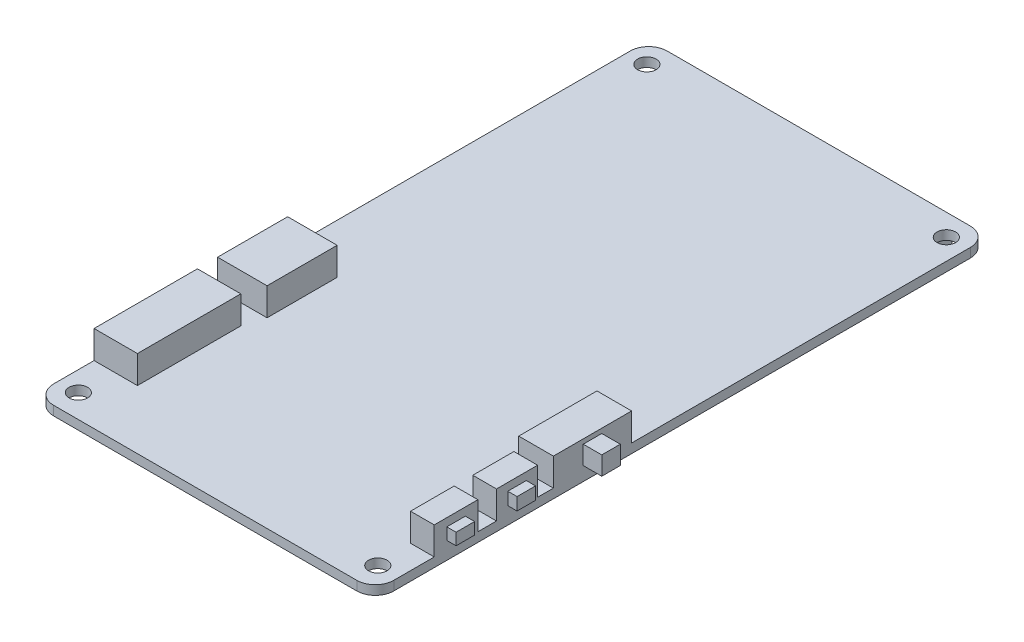
SolidWorks part; units mm, degrees
ref_plane "Front Plane" through (0, 0, 0) normal (0, 0, 1) x (1, 0, 0)
ref_plane "Top Plane" through (0, 0, 0) normal (0, 1, 0) x (1, 0, 0)
ref_plane "Right Plane" through (0, 0, 0) normal (1, 0, 0) x (0, 0, -1)
sketch "Sketch5" plane through (0, 0, 0) normal (0, 1, 0) x (1, 0, 0)
  line L1 (0, 0) -> (36.75, 0)
  line L2 (0, 0) -> (0, 66.29)
  line L3 (0, 66.29) -> (36.75, 66.29)
  line L4 (36.75, 0) -> (36.75, 66.29)
  dimension "D1" = 36.75
  dimension "D2" = 66.29
extrude "Boss-Extrude3" add sketch "Sketch5" along normal blind 1
fillet "Fillet1" radius 2 1 edges at (0, 0.5, 0)
fillet "Fillet2" radius 2 3 edges at (0, 0.5, -66.29) (36.75, 0.5, -66.29) (36.75, 0.5, 0)
sketch "Sketch7" plane through (0, 1, 0) normal (0, 1, 0) x (1, 0, 0)
  line L0 (0, 2.52) -> (36.75, 2.52)
  line L1 (0, 64.29) -> (0, 2) construction
  line L2 (36.75, 2) -> (36.75, 64.29) construction
  line L3 (2, 0) -> (34.75, 0) construction
  line L4 (0, 63.94) -> (36.75, 63.94)
  line L5 (34.75, 66.29) -> (2, 66.29) construction
  line L6 (2.15, 66.29) -> (2.15, 0)
  line L7 (34.5, 66.29) -> (34.5, 0)
  circle A0 centre (2.15, 63.94) radius 1
  circle A1 centre (34.5, 63.94) radius 1
  circle A2 centre (2.15, 2.52) radius 1
  circle A3 centre (34.5, 2.52) radius 1
  point P18 (0, 0)
  dimension "D5" = 2
  dimension "D6" = 2
  dimension "D7" = 2
  dimension "D8" = 2
  dimension "D1" = 2.52
  dimension "D2" = 2.35
  dimension "D3" = 2.15
  dimension "D4" = 2.25
extrude "Cut-Extrude1" cut sketch "Sketch7" against normal blind 2 contours A0 | A1 | A3 | A2
sketch "Sketch9" plane through (0, 1, 0) normal (0, 1, 0) x (1, 0, 0)
  line L0 (41.1667, 224.0946) -> (205.8333, 224.0946) construction
  line L1 (0, 64.29) -> (0, 2) construction
  line L2 (0, 6.3692) -> (4.6839, 6.3692)
  line L3 (0, 6.3692) -> (0, 17.5362)
  line L4 (0, 17.5362) -> (4.6839, 17.5362)
  line L5 (4.6839, 6.3692) -> (4.6839, 17.5362)
  line L6 (2, 0) -> (34.75, 0) construction
  line L7 (36.75, 2) -> (36.75, 64.29) construction
  line L8 (0, 27.2836) -> (5.3464, 27.2836)
  line L9 (0, 27.2836) -> (0, 19.7128)
  line L10 (0, 19.7128) -> (5.3464, 19.7128)
  line L11 (5.3464, 27.2836) -> (5.3464, 19.7128)
  line L12 (36.75, 27.6919) -> (33.0063, 27.6919)
  line L13 (36.75, 27.6919) -> (36.75, 19.2413)
  line L14 (36.75, 19.2413) -> (33.0063, 19.2413)
  line L15 (33.0063, 27.6919) -> (33.0063, 19.2413)
  line L17 (36.75, 17.5362) -> (34.1882, 17.5362)
  line L18 (36.75, 17.5362) -> (36.75, 13.0955)
  line L19 (36.75, 13.0955) -> (34.1882, 13.0955)
  line L20 (34.1882, 17.5362) -> (34.1882, 13.0955)
  line L21 (36.75, 11.0862) -> (34.1882, 11.0862)
  line L22 (36.75, 11.0862) -> (36.75, 6.3692)
  line L23 (36.75, 6.3692) -> (34.1882, 6.3692)
  line L24 (34.1882, 11.0862) -> (34.1882, 6.3692)
  point P28 (0, 0)
  point P29 (4.6839, 17.5362)
  point P30 (0, 0)
  line M15 (0, 64.29) -> (0, 2)
  line M19 (36.75, 2) -> (36.75, 64.29)
  dimension "D1" = 11.1669
  dimension "D2" = 4.6839
  dimension "D3" = 6.3692
  dimension "D4" = 5.3464
  dimension "D5" = 7.5708
  dimension "D6" = 19.7128
  dimension "D7" = 3.7437
  dimension "D8" = 8.4506
  dimension "D9" = 19.2413
extrude "Boss-Extrude5" add sketch "Sketch9" along normal blind 3 contours L2 L5 L4 M15 | L12 L15 L14 M19 | L17 L20 L19 M19 | L21 L24 L23 M19 | L8 L11 L10 L9
sketch "Sketch11" plane through (36.75, 0, 0) normal (1, 0, 0) x (0, 0, -1)
  line L0 (11.0862, 1) -> (6.3692, 4) construction
  line L1 (11.0862, 4) -> (6.3692, 1) construction
  line L2 (13.0955, 4) -> (17.5362, 1) construction
  line L3 (13.0955, 1) -> (17.5362, 4) construction
  line L4 (17.5362, 4) -> (17.5362, 1) construction
  line L6 (7.7277, 1.864) -> (9.7277, 1.864)
  line L7 (7.7277, 1.864) -> (7.7277, 3.136)
  line L8 (7.7277, 3.136) -> (9.7277, 3.136)
  line L9 (9.7277, 1.864) -> (9.7277, 3.136)
  line L10 (7.7277, 1.864) -> (9.7277, 3.136) construction
  line L11 (7.7277, 3.136) -> (9.7277, 1.864) construction
  line L12 (14.3158, 1.8244) -> (16.3158, 1.8244)
  line L13 (14.3158, 1.8244) -> (14.3158, 3.1756)
  line L14 (14.3158, 3.1756) -> (16.3158, 3.1756)
  line L15 (16.3158, 1.8244) -> (16.3158, 3.1756)
  line L16 (14.3158, 1.8244) -> (16.3158, 3.1756) construction
  line L17 (14.3158, 3.1756) -> (16.3158, 1.8244) construction
  point P13 (15.3158, 2.5)
  point P17 (8.7277, 2.5)
  point P18 (8.7277, 2.5)
  point P25 (15.3158, 2.5)
  dimension "D1" = 2
  dimension "D2" = 2
extrude "Boss-Extrude6" add sketch "Sketch11" along normal blind 1
sketch "Sketch12" plane through (36.75, 0, 0) normal (1, 0, 0) x (0, 0, -1)
  line L0 (19.2413, 4) -> (27.6919, 1) construction
  line L1 (27.6919, 4) -> (19.2413, 1) construction
  line L3 (22.4666, 1.5) -> (24.4666, 1.5)
  line L4 (22.4666, 1.5) -> (22.4666, 3.5)
  line L5 (22.4666, 3.5) -> (24.4666, 3.5)
  line L6 (24.4666, 1.5) -> (24.4666, 3.5)
  line L7 (22.4666, 1.5) -> (24.4666, 3.5) construction
  line L8 (22.4666, 3.5) -> (24.4666, 1.5) construction
  point P8 (23.4666, 2.5)
  dimension "D1" = 2
  dimension "D2" = 2
extrude "Boss-Extrude7" add sketch "Sketch12" along normal blind 2
sketch "Sketch13" plane through (0, 0, 0) normal (0, -1, 0) x (1, 0, 0)
  line L0 (36.75, -65.79) -> (0, -65.79) construction
  line L1 (36.75, -2) -> (36.75, -64.29) construction
  line L2 (0, -64.29) -> (0, -2) construction
  line L3 (33.25, -66.29) -> (33.25, 0) construction
  line L4 (34.75, -66.29) -> (2, -66.29) construction
  line L5 (2, 0) -> (34.75, 0) construction
  line L6 (4, -66.29) -> (4, 0) construction
  line L7 (36.75, -6.5) -> (0, -6.5) construction
  line L9 (33.25, -65.79) -> (4, -65.79)
  line L10 (33.25, -65.79) -> (33.25, -6.5)
  line L11 (33.25, -6.5) -> (4, -6.5)
  line L12 (4, -65.79) -> (4, -6.5)
  point P20 (0, 0)
  point P21 (0, 0)
  dimension "D1" = 3.5
  dimension "D2" = 4
  dimension "D3" = 0.5
  dimension "D4" = 6.5
extrude "Boss-Extrude8" add sketch "Sketch13" along normal blind 1.5
